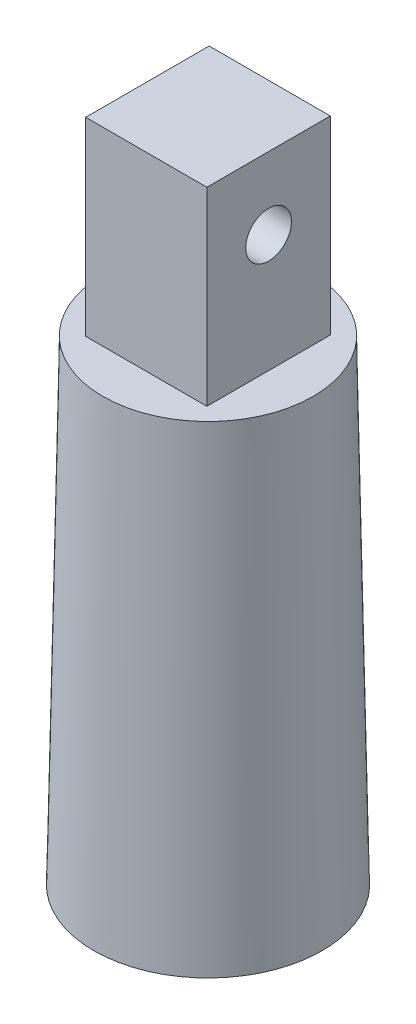
SolidWorks part; units mm, degrees
ref_plane "Front Plane" through (0, 0, 0) normal (0, 0, 1) x (1, 0, 0)
ref_plane "Top Plane" through (0, 0, 0) normal (0, 1, 0) x (1, 0, 0)
ref_plane "Right Plane" through (0, 0, 0) normal (1, 0, 0) x (0, 0, -1)
sketch "Sketch1" plane through (0, 0, 0) normal (0, 1, 0) x (1, 0, 0)
  circle A0 centre (0, 0) radius 5
  dimension "D1" = 10
ref_plane "Plane1" through (0, 20.8, 0) normal (0, 1, 0) x (1, 0, 0)
sketch "Sketch2" plane through (0, 20.8, 0) normal (0, 1, 0) x (1, 0, 0)
  circle A0 centre (0, 0) radius 4.6
  dimension "D1" = 9.2
loft "Loft1" add profiles "Sketch1", "Sketch2"
sketch "Sketch3" plane through (0, 20.8, 0) normal (0, 1, 0) x (1, 0, 0)
  line L0 (-5.5001, 0) -> (5.5001, 0) construction
  line L1 (-2.65, 2.7) -> (2.65, 2.7)
  line L2 (-2.65, 2.7) -> (-2.65, -2.7)
  line L3 (-2.65, -2.7) -> (2.65, -2.7)
  line L4 (2.65, 2.7) -> (2.65, -2.7)
  line L5 (0, -5.5001) -> (0, 5.5001) construction
  point P4 (2.65, 0)
  point P7 (0, 2.7)
  dimension "D1" = 5.4
  dimension "D2" = 5.3
extrude "Boss-Extrude1" add sketch "Sketch3" along normal blind 8.3
sketch "Sketch4" plane through (-2.65, 0, 0) normal (-1, 0, 0) x (0, 0, 1)
  line L0 (0, -5.5001) -> (0, 5.5001) construction
  line L1 (5.5001, 20.8) -> (-5.5001, 20.8) construction
  circle A0 centre (0, 25.95) radius 1
  dimension "D2" = 2
  dimension "D1" = 5.15
extrude "Cut-Extrude1" cut sketch "Sketch4" against normal through all
